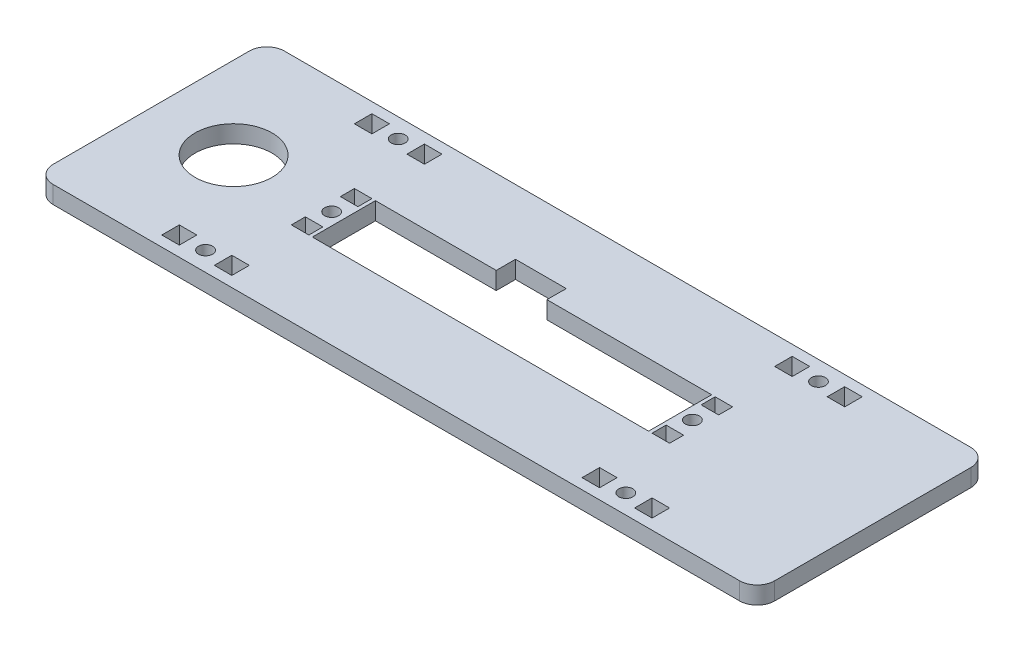
SolidWorks part; units mm, degrees
ref_plane "Front Plane" through (0, 0, 0) normal (0, 0, 1) x (1, 0, 0)
ref_plane "Top Plane" through (0, 0, 0) normal (0, 1, 0) x (1, 0, 0)
ref_plane "Right Plane" through (0, 0, 0) normal (1, 0, 0) x (0, 0, -1)
sketch "Sketch1" plane through (0, 0, 0) normal (0, 1, 0) x (1, 0, 0)
  line L0 (5.1027, 46.1563) -> (5.1027, -19.8437) construction
  line L1 (-97.8973, 46.1563) -> (108.1027, 46.1563)
  line L2 (-97.8973, 46.1563) -> (-97.8973, -19.8437)
  line L3 (-97.8973, -19.8437) -> (108.1027, -19.8437)
  line L4 (108.1027, 46.1563) -> (108.1027, -19.8437)
  line L5 (-97.8973, 13.1563) -> (108.1027, 13.1563) construction
  line L6 (60.1027, 38.1563) -> (55.1027, 38.1563)
  line L7 (-64.8973, 43.1563) -> (-59.8973, 43.1563)
  line L8 (-64.8973, 43.1563) -> (-64.8973, 38.1563)
  line L9 (-64.8973, 38.1563) -> (-59.8973, 38.1563)
  line L10 (-59.8973, 43.1563) -> (-59.8973, 38.1563)
  line L11 (-49.8973, 43.1563) -> (-44.8973, 43.1563)
  line L12 (-49.8973, 43.1563) -> (-49.8973, 38.1563)
  line L13 (-49.8973, 38.1563) -> (-44.8973, 38.1563)
  line L14 (-44.8973, 43.1563) -> (-44.8973, 38.1563)
  line L15 (55.1027, 43.1563) -> (55.1027, 38.1563)
  line L16 (60.1027, 43.1563) -> (55.1027, 43.1563)
  line L17 (60.1027, 43.1563) -> (60.1027, 38.1563)
  line L18 (70.1027, 43.1563) -> (70.1027, 38.1563)
  line L19 (75.1027, 43.1563) -> (70.1027, 43.1563)
  line L20 (75.1027, 43.1563) -> (75.1027, 38.1563)
  line L21 (75.1027, 38.1563) -> (70.1027, 38.1563)
  line L22 (75.1027, -16.8437) -> (75.1027, -11.8437)
  line L23 (75.1027, -11.8437) -> (70.1027, -11.8437)
  line L24 (75.1027, -16.8437) -> (70.1027, -16.8437)
  line L25 (70.1027, -16.8437) -> (70.1027, -11.8437)
  line L26 (60.1027, -16.8437) -> (60.1027, -11.8437)
  line L27 (60.1027, -11.8437) -> (55.1027, -11.8437)
  line L28 (55.1027, -16.8437) -> (55.1027, -11.8437)
  line L29 (60.1027, -16.8437) -> (55.1027, -16.8437)
  line L30 (-49.8973, -16.8437) -> (-44.8973, -16.8437)
  line L31 (-44.8973, -16.8437) -> (-44.8973, -11.8437)
  line L32 (-49.8973, -11.8437) -> (-44.8973, -11.8437)
  line L33 (-49.8973, -16.8437) -> (-49.8973, -11.8437)
  line L34 (-64.8973, -16.8437) -> (-59.8973, -16.8437)
  line L35 (-64.8973, -16.8437) -> (-64.8973, -11.8437)
  line L36 (-64.8973, -11.8437) -> (-59.8973, -11.8437)
  line L37 (-59.8973, -16.8437) -> (-59.8973, -11.8437)
  line L39 (-97.8973, 13.1563) -> (108.1027, 13.1563) construction
  line L41 (-46.3973, 13.1563) -> (-46.3973, 6.4162) construction
  line L44 (-43.8973, 22.1563) -> (-48.8973, 22.1563)
  line L46 (-43.8973, 18.1563) -> (-48.8973, 18.1563)
  line L47 (-48.8973, 22.1563) -> (-48.8973, 18.1563)
  line L50 (-43.8973, 22.1563) -> (-43.8973, 18.1563)
  line L52 (-48.8973, 4.1563) -> (-48.8973, 8.1563)
  line L53 (-43.8973, 4.1563) -> (-43.8973, 8.1563)
  line L54 (-43.8973, 8.1563) -> (-48.8973, 8.1563)
  line L55 (-43.8973, 4.1563) -> (-48.8973, 4.1563)
  line L56 (54.1027, 4.1563) -> (54.1027, 8.1563)
  line L57 (54.1027, 4.1563) -> (59.1027, 4.1563)
  line L58 (59.1027, 4.1563) -> (59.1027, 8.1563)
  line L59 (54.1027, 8.1563) -> (59.1027, 8.1563)
  line L60 (54.1027, 18.1563) -> (59.1027, 18.1563)
  line L61 (54.1027, 22.1563) -> (54.1027, 18.1563)
  line L62 (54.1027, 22.1563) -> (59.1027, 22.1563)
  line L63 (59.1027, 22.1563) -> (59.1027, 18.1563)
  line L64 (-43.8973, 22.1563) -> (-42.8973, 22.1563) construction
  line L65 (54.1027, 4.1563) -> (53.1027, 4.1563) construction
  line L66 (6.0682, 4.1563) -> (53.1027, 4.1563)
  line L67 (-42.8973, 22.1563) -> (-8.3973, 22.1563)
  line L68 (-42.8973, 22.1563) -> (-42.8973, 4.1563)
  line L69 (-42.8973, 4.1563) -> (-8.3973, 4.1563)
  line L70 (53.1027, 22.1563) -> (53.1027, 4.1563)
  line L75 (6.0682, 22.1563) -> (6.1027, 27.6562)
  line L76 (-8.3973, 27.6563) -> (6.1027, 27.6562)
  line L77 (-8.3973, 22.1563) -> (-8.3973, 27.6563)
  line L78 (6.0682, 22.1563) -> (53.1027, 22.1563)
  line L79 (-8.3973, 4.1563) -> (6.0682, 4.1563)
  circle A0 centre (-54.8973, 40.6563) radius 2
  circle A1 centre (-54.8973, -14.3437) radius 2
  circle A2 centre (65.1027, -14.3437) radius 2
  circle A3 centre (65.1027, 40.6563) radius 2
  circle A7 centre (-74.3973, 13.1563) radius 11
  circle A8 centre (-46.3973, 13.1563) radius 2
  circle A9 centre (56.6027, 13.1563) radius 2
  point P36 (-59.8973, -11.8437)
  point P59 (-46.3973, 18.1563)
  point P60 (-46.3973, 22.1563)
  dimension "D7" = 4
  dimension "D8" = 4
  dimension "D12" = 22
  dimension "D1" = 206
  dimension "D2" = 66
  dimension "D3" = 5
  dimension "D4" = 10
  dimension "D5" = 3
  dimension "D6" = 50
  dimension "D9" = 4
  dimension "D10" = 5
  dimension "D11" = 5.5
  dimension "D13" = 5
  dimension "D14" = 54
  dimension "D15" = 16
  dimension "D16" = 1
  dimension "D17" = 1
  dimension "D18" = 34.5
  dimension "D19" = 14.5
  dimension "D20" = 5.5
extrude "Boss-Extrude4" add sketch "Sketch1" along normal blind 5
fillet "Fillet9" radius 5 4 edges at (108.1027, 2.5, -46.1563) (108.1027, 2.5, 19.8437) (-97.8973, 2.5, -46.1563) (-97.8973, 2.5, 19.8437)
ref_plane "Plane1" through (-42.8973, 5, -4.1563) normal (1, 0, 0) x (0, 0, -1)
sketch "Sketch2" plane through (-42.8973, 5, -4.1563) normal (1, 0, 0) x (0, 0, -1)
